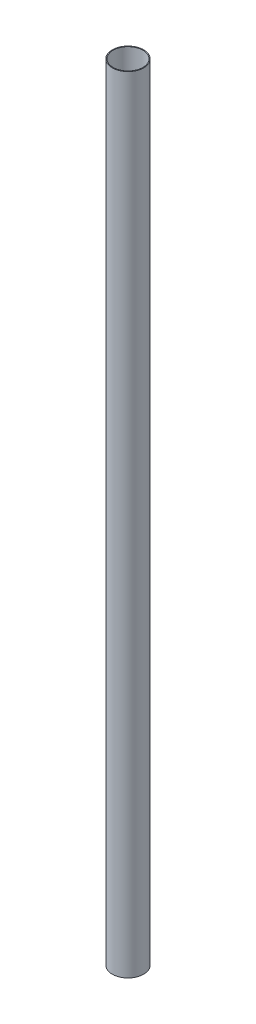
SolidWorks part; units mm, degrees
material "ПВХ 0.007 Смягченный"
ref_plane "Спереди" through (0, 0, 0) normal (0, 0, 1) x (1, 0, 0)
ref_plane "Сверху" through (0, 0, 0) normal (0, 1, 0) x (1, 0, 0)
ref_plane "Справа" through (0, 0, 0) normal (1, 0, 0) x (0, 0, -1)
sketch "Эскиз1" plane through (0, 0, 0) normal (0, 1, 0) x (1, 0, 0)
  circle A0 centre (0, 0) radius 20
  circle A1 centre (0, 0) radius 19
  dimension "ExDBody" = 40
  dimension "InDBody" = 38
extrude "Бобышка-Вытянуть1" add sketch "Эскиз1" along normal blind 1000
